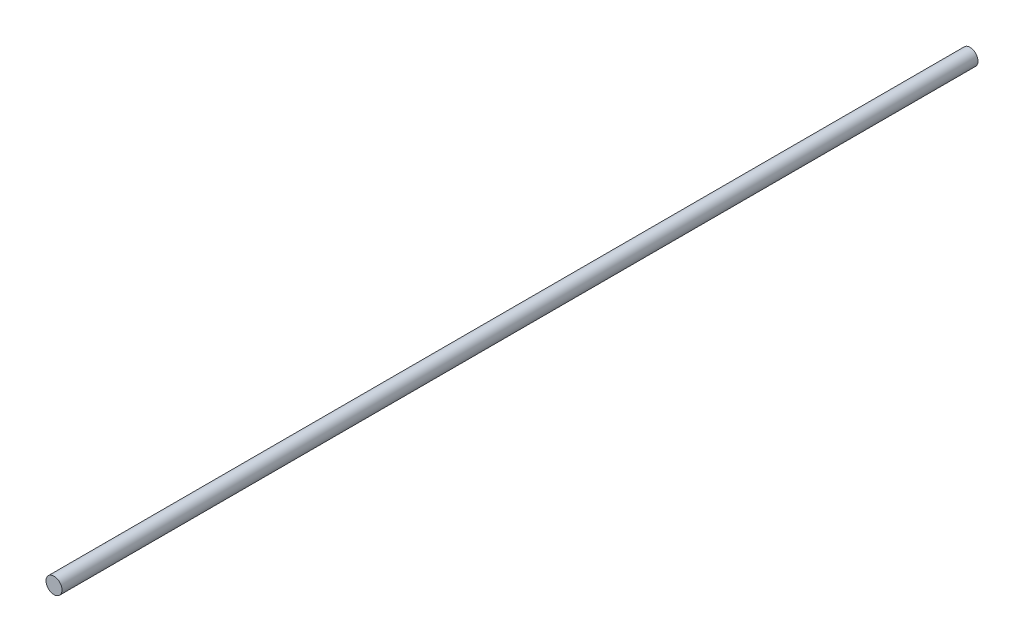
SolidWorks part; units mm, degrees
material "6063-T4"
ref_plane "Front Plane" through (0, 0, 0) normal (0, 0, 1) x (1, 0, 0)
ref_plane "Top Plane" through (0, 0, 0) normal (0, 1, 0) x (1, 0, 0)
ref_plane "Right Plane" through (0, 0, 0) normal (1, 0, 0) x (0, 0, -1)
sketch "Sketch1" plane through (0, 0, 0) normal (0, 0, 1) x (1, 0, 0)
  circle A0 centre (0, 0) radius 2.5
  dimension "D1" = 5
extrude "Boss-Extrude1" add sketch "Sketch1" along normal blind 286
